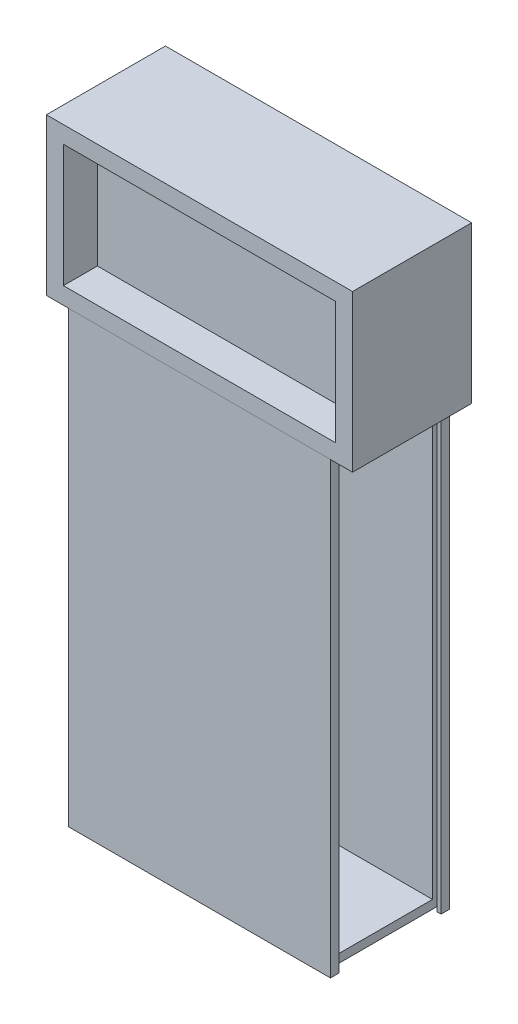
SolidWorks part; units mm, degrees
ref_plane "Front Plane" through (0, 0, 0) normal (0, 0, 1) x (1, 0, 0)
ref_plane "Top Plane" through (0, 0, 0) normal (0, 1, 0) x (1, 0, 0)
ref_plane "Right Plane" through (0, 0, 0) normal (1, 0, 0) x (0, 0, -1)
sketch "Sketch1" plane through (0, 0, 0) normal (0, 0, 1) x (1, 0, 0)
  line L1 (-38.5, -66) -> (38.5, -66)
  line L2 (-38.5, -66) -> (-38.5, 66)
  line L3 (-38.5, 66) -> (38.5, 66)
  line L4 (38.5, -66) -> (38.5, 66)
  line L5 (-38.5, -66) -> (38.5, 66) construction
  line L6 (-38.5, 66) -> (38.5, -66) construction
  point P0 (0, 0)
  dimension "D1" = 77
  dimension "D2" = 132
extrude "Boss-Extrude1" add sketch "Sketch1" along normal blind 35
sketch "Sketch2" plane through (0, 66, 0) normal (0, 1, 0) x (1, 0, 0)
  line L0 (0, 0) -> (0, -35) construction
  line L1 (-38.5, 0) -> (38.5, 0)
  line L2 (-38.5, 0) -> (-38.5, -35)
  line L3 (-38.5, -35) -> (38.5, -35)
  line L4 (38.5, 0) -> (38.5, -35)
  line L6 (45, -35) -> (-45, -35)
  line L7 (45, -35) -> (45, 0)
  line L8 (45, 0) -> (-45, 0)
  line L9 (-45, -35) -> (-45, 0)
  line L10 (45, -35) -> (-45, 0) construction
  line L11 (45, 0) -> (-45, -35) construction
  point P9 (0, -17.5)
  line M1 (38.5, 0) -> (-38.5, 0)
  line M2 (-38.5, 0) -> (-38.5, -35)
  line M3 (-38.5, -35) -> (38.5, -35)
  line M4 (38.5, -35) -> (38.5, 0)
  dimension "D1" = 90
extrude "Boss-Extrude3" add sketch "Sketch2" along normal blind 46 separate body contours M4 M1 M2 M3 | L9 L6 L8 M2 | L7 L8 L6 M4
shell "Shell4" thickness 2.5
sketch "Sketch3" plane through (0, 0, 35) normal (0, 0, 1) x (1, 0, 0)
  line L0 (0, 112) -> (0, 66) construction
  line L1 (-45, 112) -> (45, 112) construction
  line L2 (38.5, 66) -> (-38.5, 66) construction
  line L4 (-40, 71) -> (40, 71)
  line L5 (-40, 71) -> (-40, 107)
  line L6 (-40, 107) -> (40, 107)
  line L7 (40, 71) -> (40, 107)
  line L8 (-40, 71) -> (40, 107) construction
  line L9 (-40, 107) -> (40, 71) construction
  point P6 (0, 89)
  dimension "D1" = 80
  dimension "D2" = 36
extrude "Cut-Extrude1" cut sketch "Sketch3" against normal blind 10
sketch "Sketch4" plane through (38.5, 0, 0) normal (1, 0, 0) x (0, 0, -1)
  line L0 (-35, 66) -> (0, 66) construction
  line L1 (-32.5, 66) -> (-2.5, 66)
  line L2 (-32.5, 66) -> (-32.5, -66)
  line L3 (-32.5, -66) -> (-2.5, -66)
  line L4 (-2.5, 66) -> (-2.5, -66)
  line L5 (-35, -66) -> (0, -66) construction
extrude "Cut-Extrude2" cut sketch "Sketch4" against normal blind 2.5
sketch "Sketch5" plane through (0, -66, 0) normal (0, -1, 0) x (1, 0, 0)
  line L0 (36, 17.5) -> (45, 17.5) construction
  line L1 (36, 32.5) -> (37.25, 32.5)
  line L2 (36, 32.5) -> (36, 33.75)
  line L3 (36, 33.75) -> (37.25, 33.75)
  line L4 (37.25, 32.5) -> (37.25, 33.75)
  line L5 (36, 32.5) -> (36, 2.5) construction
  line L6 (45, 35) -> (45, 0) construction
  line L7 (36, 1.25) -> (37.25, 1.25)
  line L8 (37.25, 2.5) -> (37.25, 1.25)
  line L9 (36, 2.5) -> (37.25, 2.5)
  line L10 (36, 2.5) -> (36, 1.25)
extrude "Cut-Extrude3" cut sketch "Sketch5" against normal up to body separate body
